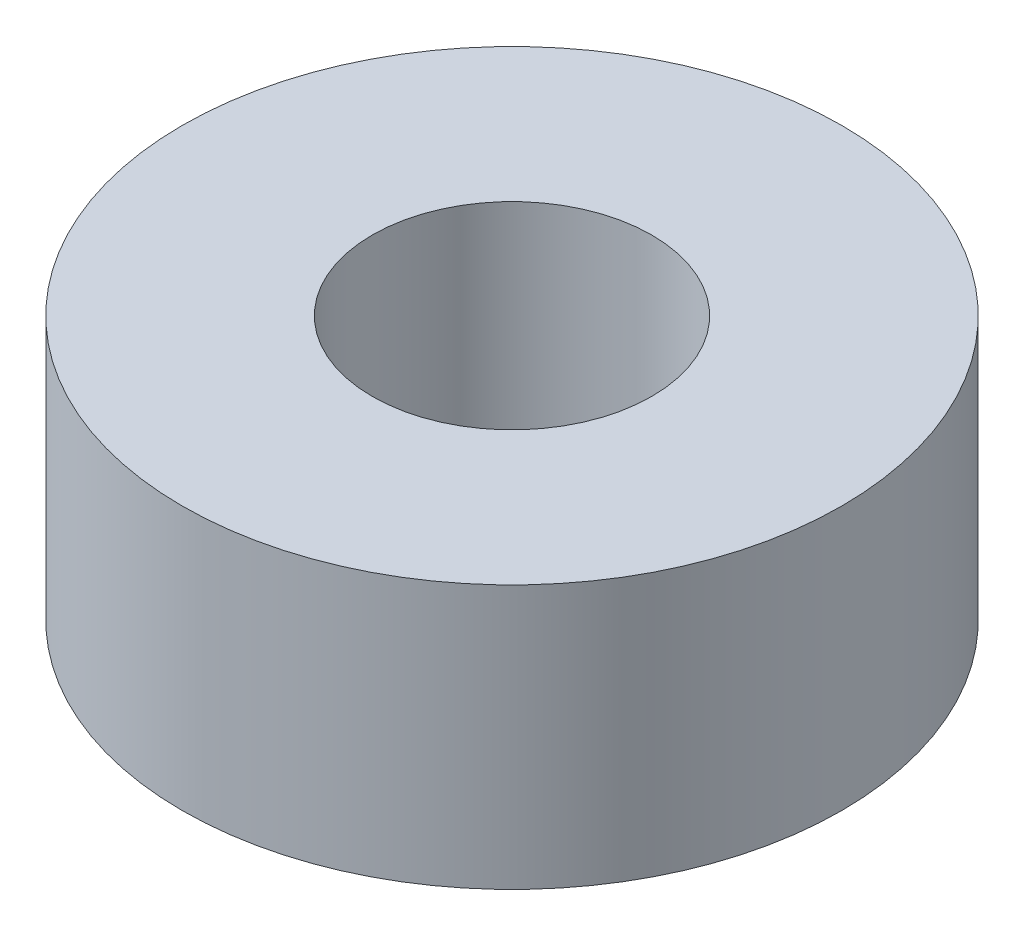
SolidWorks part; units mm, degrees
material "ABS"
ref_plane "Front Plane" through (0, 0, 0) normal (0, 0, 1) x (1, 0, 0)
ref_plane "Top Plane" through (0, 0, 0) normal (0, 1, 0) x (1, 0, 0)
ref_plane "Right Plane" through (0, 0, 0) normal (1, 0, 0) x (0, 0, -1)
sketch "Sketch1" plane through (0, 0, 0) normal (0, 1, 0) x (1, 0, 0)
  circle A0 centre (0, 0) radius 7.9375
  circle A1 centre (0, 0) radius 3.3655
  dimension "D1" = 15.875
  dimension "D2" = 6.731
extrude "Boss-Extrude1" add sketch "Sketch1" along normal blind 6.35
